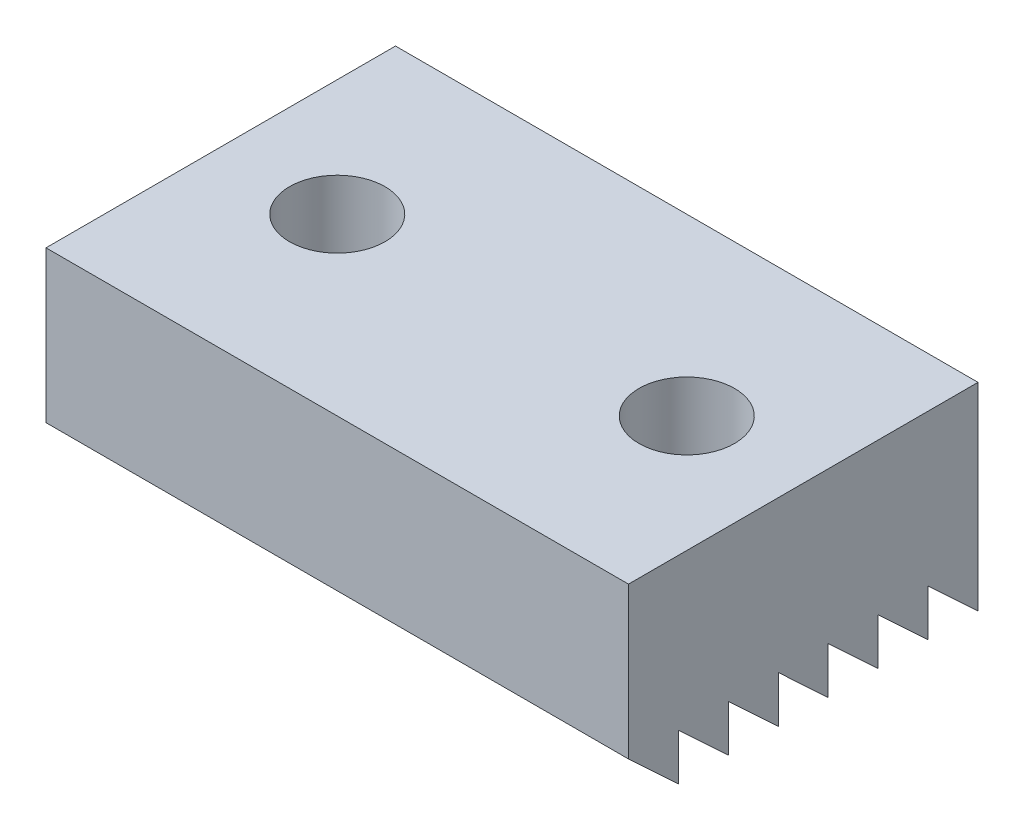
SolidWorks part; units mm, degrees
ref_plane "Alzado" through (0, 0, 0) normal (0, 0, 1) x (1, 0, 0)
ref_plane "Planta" through (0, 0, 0) normal (0, 1, 0) x (1, 0, 0)
ref_plane "Vista lateral" through (0, 0, 0) normal (1, 0, 0) x (0, 0, -1)
sketch "Croquis1" plane through (0, 0, 0) normal (0, 1, 0) x (1, 0, 0)
  line L0 (0, 7.5) -> (5, 7.5) construction
  line L1 (0, 0) -> (25, 0)
  line L2 (0, 0) -> (0, 15)
  line L3 (0, 15) -> (25, 15)
  line L4 (25, 0) -> (25, 15)
  line L5 (5, 7.5) -> (20, 7.5) construction
  line L6 (20, 7.5) -> (25, 7.5) construction
  line L7 (12.5, 7.5) -> (12.5, 15) construction
  circle A0 centre (5, 7.5) radius 2.05
  circle A1 centre (20, 7.5) radius 2.05
  dimension "D3" = 4.1
  dimension "D1" = 25
  dimension "D2" = 15
  dimension "D4" = 15
extrude "Saliente-Extruir1" add sketch "Croquis1" along normal blind 5
sketch "Croquis2" plane through (0, 0, 0) normal (-1, 0, 0) x (0, 0, 1)
  line L0 (-15, 0) -> (-15, -3.5)
  line L1 (-15, -3.5) -> (-12.8571, -1.5)
  line L2 (-12.8571, -1.5) -> (-12.8571, -3.5)
  line L3 (-12.8571, -3.5) -> (-10.7143, -1.5)
  line L4 (-10.7143, -1.5) -> (-10.7143, -3.5)
  line L5 (-10.7143, -3.5) -> (-8.5714, -1.5)
  line L6 (-8.5714, -1.5) -> (-8.5714, -3.5)
  line L7 (-8.5714, -3.5) -> (-6.4286, -1.5)
  line L8 (-6.4286, -1.5) -> (-6.4286, -3.5)
  line L9 (-6.4286, -3.5) -> (-4.2857, -1.5)
  line L10 (-4.2857, -1.5) -> (-4.2857, -3.5)
  line L11 (-4.2857, -3.5) -> (-2.1429, -1.5)
  line L12 (-2.1429, -1.5) -> (-2.1429, -3.5)
  line L15 (0, 0) -> (-15, 0)
  line L16 (-15, -3.5) -> (-12.8571, -3.5) construction
  line L17 (-12.8571, -3.5) -> (-10.7143, -3.5) construction
  line L18 (-10.7143, -3.5) -> (-8.5714, -3.5) construction
  line L19 (-6.4286, -3.5) -> (-8.5714, -3.5) construction
  line L20 (-6.4286, -3.5) -> (-4.2857, -3.5) construction
  line L21 (-4.2857, -3.5) -> (-2.1429, -3.5) construction
  line L23 (-2.1429, -3.5) -> (0, -1.5)
  line L24 (0, -1.5) -> (0, 0)
  line L25 (0, -1.5) -> (0, -3.5) construction
  line L26 (0, -3.5) -> (-2.1429, -3.5) construction
  line L27 (0, -1.5) -> (-2.1429, -1.5) construction
  dimension "D1" = 3.5
  dimension "D2" = 2
extrude "Saliente-Extruir2" add sketch "Croquis2" against normal up to surface (25 mm away) up to face at (25, 2.5, -7.5)
sketch "Croquis3" plane through (0, 5, 0) normal (0, 1, 0) x (1, 0, 0)
  circle A0 centre (5, 7.5) radius 2.05 construction
  circle A1 centre (5, 7.5) radius 2.05
  circle A2 centre (20, 7.5) radius 2.05 construction
  circle A3 centre (20, 7.5) radius 2.05
extrude "Cortar-Extruir1" cut sketch "Croquis3" against normal blind 29
